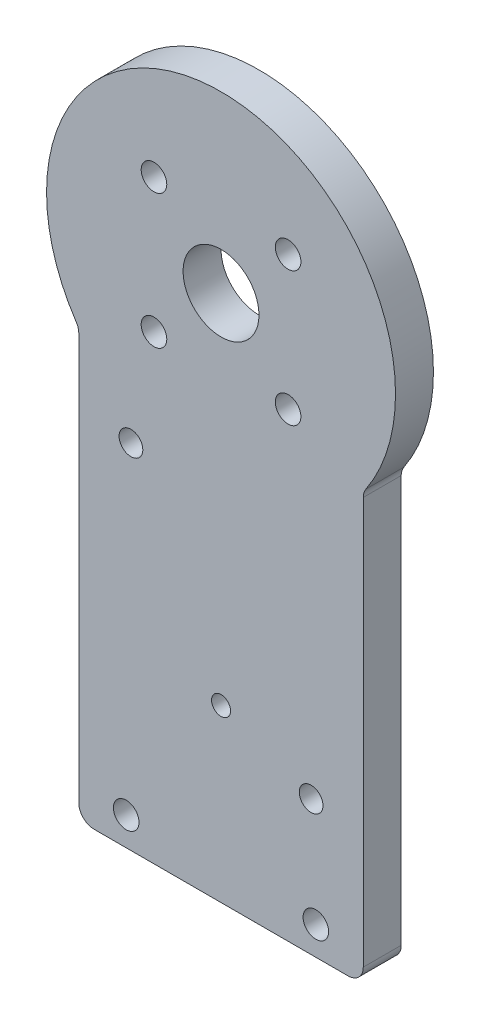
SolidWorks part; units mm, degrees
material "Aleación 1060"
ref_plane "Alzado" through (0, 0, 0) normal (0, 0, 1) x (1, 0, 0)
ref_plane "Planta" through (0, 0, 0) normal (0, 1, 0) x (1, 0, 0)
ref_plane "Vista lateral" through (0, 0, 0) normal (1, 0, 0) x (0, 0, -1)
sketch "Croquis1" plane through (0, 0, 0) normal (0, 0, 1) x (1, 0, 0)
  line L0 (0, 0) -> (-7.0711, -7.0711) construction
  line L1 (0, -18.4) -> (-15, -18.4) construction
  line L2 (-15, -10.6565) -> (-15, -55.6565)
  line L3 (0, -4) -> (0, -18.4) construction
  line L4 (15, -10.6565) -> (15, -55.6565)
  line L5 (-15, -55.6565) -> (15, -55.6565)
  line L6 (0, -55.6565) -> (0, -33.1565) construction
  line L7 (0, -33.1565) -> (12.5, -33.1565) construction
  line L8 (12.5, -33.1565) -> (12.5, -49.91) construction
  line L9 (12.5, -49.91) -> (-12.5, -49.91) construction
  line L10 (-12.5, -49.91) -> (-12.5, -9.91) construction
  line L11 (-12.5, -9.91) -> (12.5, -9.91) construction
  line L12 (12.5, -9.91) -> (12.5, -33.1565) construction
  arc A0 (15, -10.6565) -> (-15, -10.6565) centre (0, 0) ccw
  circle A1 centre (-7.0711, -7.0711) radius 1.35
  circle A2 centre (-7.0711, 7.0711) radius 1.35
  circle A3 centre (7.0711, 7.0711) radius 1.35
  circle A4 centre (7.0711, -7.0711) radius 1.35
  circle A5 centre (0, 0) radius 4
  circle A6 centre (-10, -52.6565) radius 1.35
  circle A7 centre (10, -52.6565) radius 1.35
  circle A8 centre (9.5, -41.434) radius 1.25
  circle A9 centre (-9.5, -18.434) radius 1.25
  circle A10 centre (-7.0711, -7.0711) radius 2.5 construction
  circle A11 centre (-10, -52.6565) radius 2.5 construction
  point P14 (0, 0)
  point P27 (15, -33.1565)
  dimension "D1" = 36.8
  dimension "D3" = 2.7
  dimension "D5" = 8
  dimension "D8" = 5
  dimension "D10" = 2.7
  dimension "D14" = 8.524
  dimension "D16" = 19
  dimension "D18" = 2.5
  dimension "D19" = 2.5
  dimension "D20" = 5
  dimension "D2" = 10
  dimension "D6" = 15
  dimension "D7" = 45
  dimension "D9" = 3
  dimension "D11" = 12.5
  dimension "D12" = 40
  dimension "D13" = 25
  dimension "D15" = 3
  dimension "D17" = 23
  dimension "D4" = 4
extrude "Saliente-Extruir1" add sketch "Croquis1" along normal blind 4
fillet "Redondeo1" radius 1.6 4 edges at (-15, -10.6565, 2) (-15, -55.6565, 2) (15, -55.6565, 2) (15, -10.6565, 2)
sketch "Croquis2" plane through (0, 0, 4) normal (0, 0, 1) x (1, 0, 0)
  line L0 (-13.4, -55.6565) -> (13.4, -55.6565) construction
  circle A0 centre (0, -37.6565) radius 1
  point P4 (0, 0)
  point P5 (0, -55.6565)
  dimension "D1" = 2
  dimension "D2" = 18
extrude "Cortar-Extruir1" cut sketch "Croquis2" against normal up to vertex (4 mm away)
